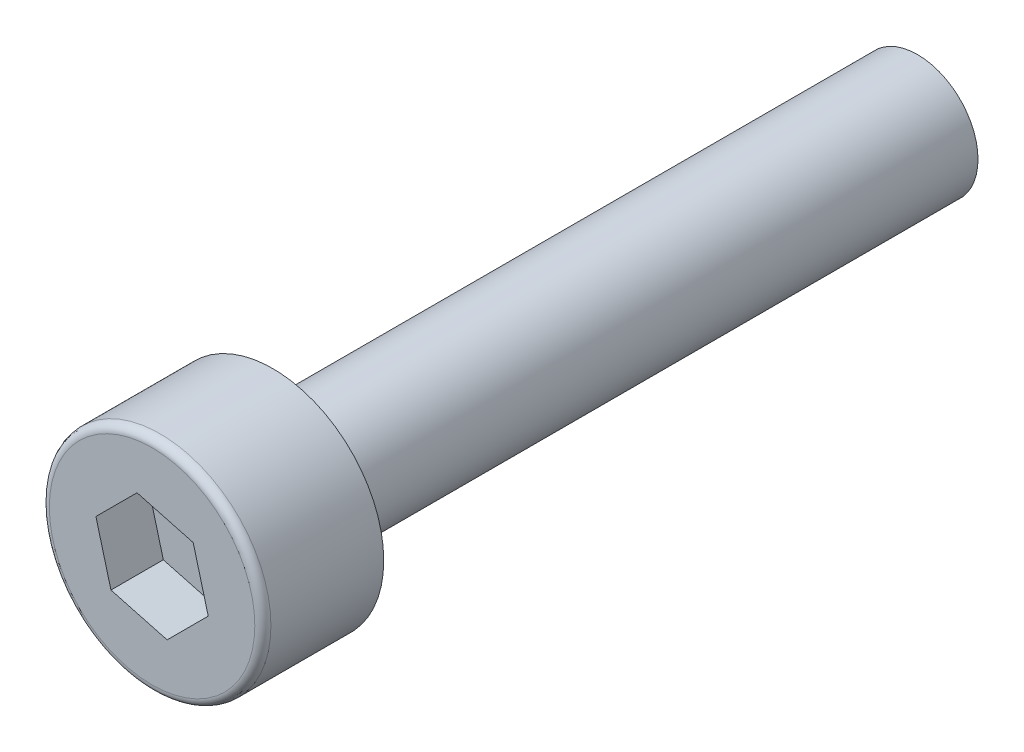
SolidWorks part; units mm, degrees
ref_plane "前视基准面" through (0, 0, 0) normal (0, 0, 1) x (1, 0, 0)
ref_plane "上视基准面" through (0, 0, 0) normal (0, 1, 0) x (1, 0, 0)
ref_plane "右视基准面" through (0, 0, 0) normal (1, 0, 0) x (0, 0, -1)
sketch "草图1" plane through (0, 0, 0) normal (0, 0, 1) x (1, 0, 0)
  circle A0 centre (0, 0) radius 2.75
  dimension "D1" = 5.5
extrude "凸台-拉伸1" add sketch "草图1" along normal blind 3
sketch "草图2" plane through (0, 0, 3) normal (0, 0, 1) x (1, 0, 0)
  line L1 (-1.0206, -1.0206) -> (0.3736, -1.3942)
  line L2 (0.3736, -1.3942) -> (1.3942, -0.3736)
  line L3 (1.3942, -0.3736) -> (1.0206, 1.0206)
  line L4 (1.0206, 1.0206) -> (-0.3736, 1.3942)
  line L5 (-0.3736, 1.3942) -> (-1.3942, 0.3736)
  line L6 (-1.3942, 0.3736) -> (-1.0206, -1.0206)
  circle A0 centre (0, 0) radius 1.25 construction
  dimension "D1" = 2.5
extrude "切除-拉伸1" cut sketch "草图2" against normal blind 1.3
sketch "草图3" plane through (0, 0, 0) normal (0, 0, -1) x (-1, 0, 0)
  circle A0 centre (0, 0) radius 1.5
  dimension "D1" = 3
extrude "凸台-拉伸2" add sketch "草图3" along normal blind 16
fillet "圆角1" radius 0.2 1 edges at (2.75, 0, 3)
